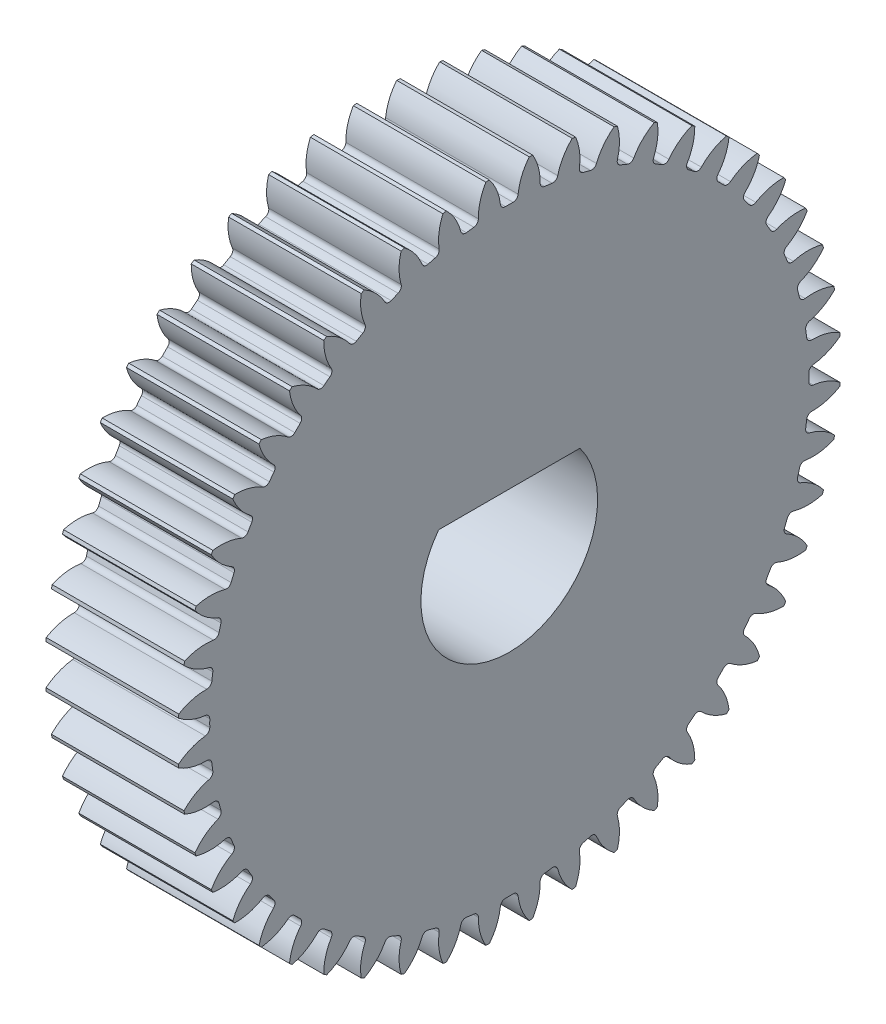
SolidWorks part; units mm, degrees
ref_plane "Front Plane" through (0, 0, 0) normal (0, 0, 1) x (1, 0, 0)
ref_plane "Top Plane" through (0, 0, 0) normal (0, 1, 0) x (1, 0, 0)
ref_plane "Right Plane" through (0, 0, 0) normal (1, 0, 0) x (0, 0, -1)
sketch "Sketch1" plane through (0, 0, 0) normal (1, 0, 0) x (0, 0, -1)
  circle A0 centre (0, 0) radius 5
  circle A1 centre (0, 0) radius 18.75
  dimension "D1" = 10
  dimension "D2" = 37.5
extrude "Boss-Extrude2" add sketch "Sketch1" along normal blind 7.5
sketch "Sketch3" plane through (7.5, 0, 0) normal (1, 0, 0) x (0, 0, -1)
  line L0 (0, 0) -> (0, 18.75) construction
  line L1 (-0.482, 16.9431) -> (0, 0) construction
  line L2 (0, 16.065) -> (-2.0038, 21.5703) construction
  circle A0 centre (0, 0) radius 18.75 construction
  arc A1 (0.482, 16.9431) -> (-0.482, 16.9431) centre (0, 0) ccw
  arc A2 (0.7015, 17.9863) -> (-0.7015, 17.9863) centre (0, 0) ccw construction
  arc A3 (1.1273, 18.7161) -> (-1.1273, 18.7161) centre (0, 0) ccw
  arc A4 (-1.1273, 18.7161) -> (-0.482, 16.9431) centre (-3.474, 16.858) cw
  arc A5 (1.1273, 18.7161) -> (0.482, 16.9431) centre (3.474, 16.858) ccw
  point P17 (-0.6613, 17.8818)
  dimension "D1" = 37.5
  dimension "D2" = 36
  dimension "D3" = 1.8
  dimension "D4" = 20
  dimension "D5" = 1.4031
extrude "Cut-Extrude1" cut sketch "Sketch3" against normal through all
fillet "Fillet1" radius 0.285 2 edges at (3.75, 16.9431, -0.482) (3.75, 16.9431, 0.482)
pattern_circular "CirPattern2" count 48 over 360 about axis through (0, 0, 0) along (1, 0, 0) of "Fillet1", "Cut-Extrude1"
sketch "Sketch4" plane through (7.5, 0, 0) normal (1, 0, 0) x (0, 0, -1)
  line L0 (-4, 3) -> (4, 3)
  circle A0 centre (0, 0) radius 5 construction
  arc A1 (-4, 3) -> (4, 3) centre (0, 0) cw
  dimension "D1" = 3
extrude "Boss-Extrude3" add sketch "Sketch4" against normal up to surface (7.5 mm away) up to face at (0, 0, -5)
equation "\"No of teeth\"= 48"
equation "\"Module\"= .75"
equation "\"Outer Diameter\"= ( \"No of teeth\" + 2 ) * \"Module\""
equation "\"Pitch Diameter\"= \"No of teeth\" * \"Module\""
equation "\"Backlash\"= 0.3 * \"Module\""
equation "\"Arc Length\"= ( ( \"Module\" * pi ) / 2 ) + \"Backlash\""
equation "\"Fillet Radius\"= 0.38 * \"Module\""
equation "\"Bore Diameter\"=10"
equation "\"Presseure angle\"= 20"
equation "\"Tooth Depth\"= IIF ( \"Module\" <= 1.25 , 2.4 * \"Module\" , 2.25 * \"Module\" )"
equation "\"D1@Sketch1\"=\"Bore Diameter\""
equation "\"D2@Sketch1\"=\"Outer Diameter\""
equation "\"D1@Sketch3\"=\"Outer Diameter\""
equation "\"D2@Sketch3\"=\"Pitch Diameter\""
equation "\"D3@Sketch3\"=\"Tooth Depth\""
equation "\"D4@Sketch3\"=\"Presseure angle\""
equation "\"D5@Sketch3\"=\"Arc Length\""
equation "\"D1@Fillet1\"=\"Fillet Radius\""
equation "\"D1@CirPattern2\"=\"No of teeth\""
